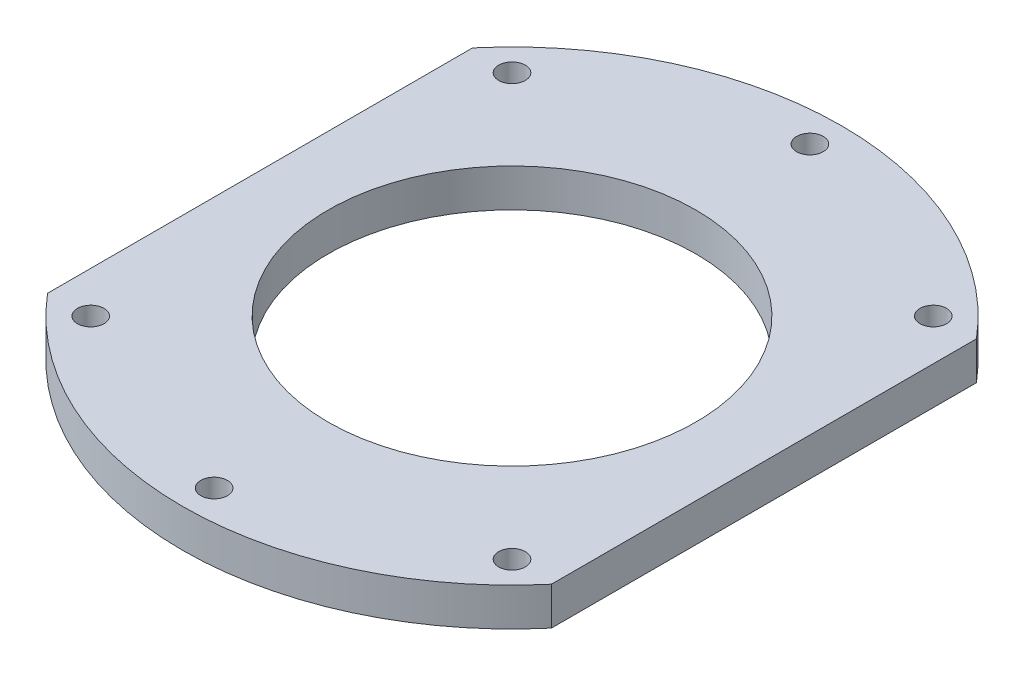
SolidWorks part; units mm, degrees
ref_plane "前视基准面" through (0, 0, 0) normal (0, 0, 1) x (1, 0, 0)
ref_plane "上视基准面" through (0, 0, 0) normal (0, 1, 0) x (1, 0, 0)
ref_plane "右视基准面" through (0, 0, 0) normal (1, 0, 0) x (0, 0, -1)
sketch "草图1" plane through (0, 0, 0) normal (0, 1, 0) x (1, 0, 0)
  circle A0 centre (0, 0) radius 29
  circle A1 centre (0, 0) radius 52
  circle A2 centre (47, 0) radius 2.1
  circle A3 centre (33.234, -33.234) radius 2.1
  circle A4 centre (0, -47) radius 2.1
  circle A5 centre (-33.234, -33.234) radius 2.1
  circle A6 centre (-47, 0) radius 2.1
  circle A7 centre (-33.234, 33.234) radius 2.1
  circle A8 centre (0, 47) radius 2.1
  circle A9 centre (33.234, 33.234) radius 2.1
  circle A10 centre (0, 0) radius 43 construction
  point P6 (52, 0)
  point P9 (43, 0)
  dimension "D1" = 58
  dimension "D2" = 86
  dimension "D3" = 4
  dimension "D4" = 4.2
  dimension "D7" = 5
  dimension "D5" = 8
extrude "凸台-拉伸1" add sketch "草图1" along normal blind 6
sketch "草图2" plane through (0, 6, 0) normal (0, 1, 0) x (1, 0, 0)
  line L1 (-39.75, -55.0176) -> (39.75, -55.0176)
  line L2 (-39.75, -55.0176) -> (-39.75, 55.0176)
  line L3 (-39.75, 55.0176) -> (39.75, 55.0176)
  line L4 (39.75, -55.0176) -> (39.75, 55.0176)
  line L5 (-39.75, -55.0176) -> (39.75, 55.0176) construction
  line L6 (-39.75, 55.0176) -> (39.75, -55.0176) construction
  point P0 (0, 0)
  dimension "D1" = 79.5
extrude "切除-拉伸-薄壁1" cut sketch "草图2" against normal blind 10 thin
